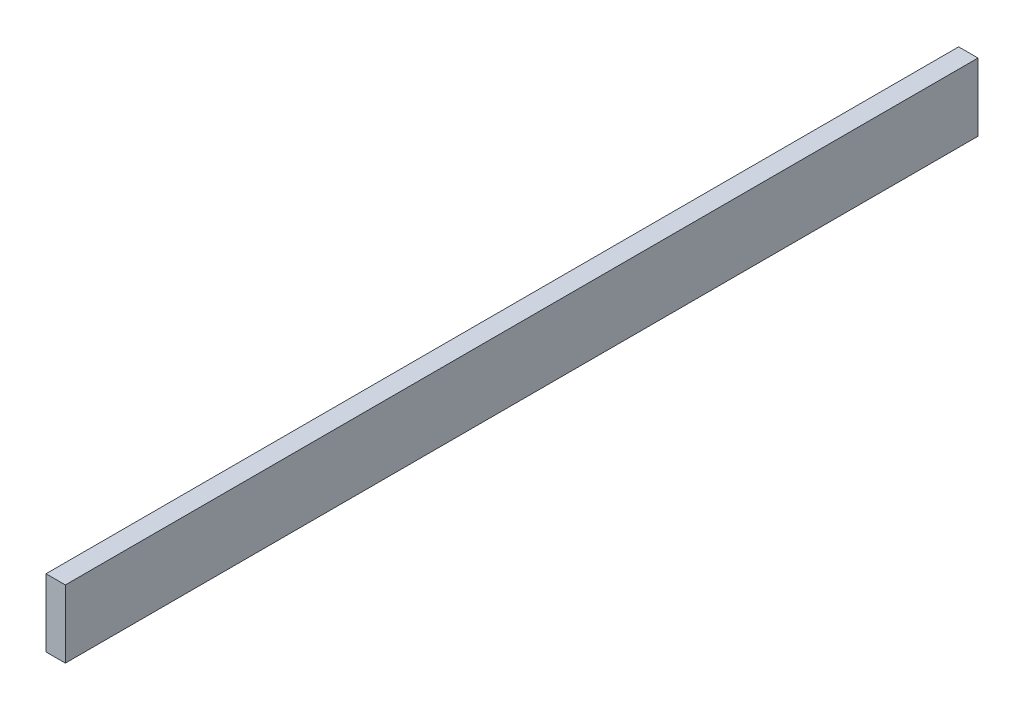
SolidWorks part; units mm, degrees
ref_plane "Front Plane" through (0, 0, 0) normal (0, 0, 1) x (1, 0, 0)
ref_plane "Top Plane" through (0, 0, 0) normal (0, 1, 0) x (1, 0, 0)
ref_plane "Right Plane" through (0, 0, 0) normal (1, 0, 0) x (0, 0, -1)
other "Configuration Table"
sketch "Sketch1" plane through (0, 0, 0) normal (0, 0, 1) x (1, 0, 0)
  line L1 (714, 1528) -> (728, 1528)
  line L2 (714, 1528) -> (714, 1577)
  line L3 (714, 1577) -> (728, 1577)
  line L4 (728, 1528) -> (728, 1577)
extrude "DET2_ray_dis_profil_sol_1" add sketch "Sketch1" against normal blind 660 separate body
